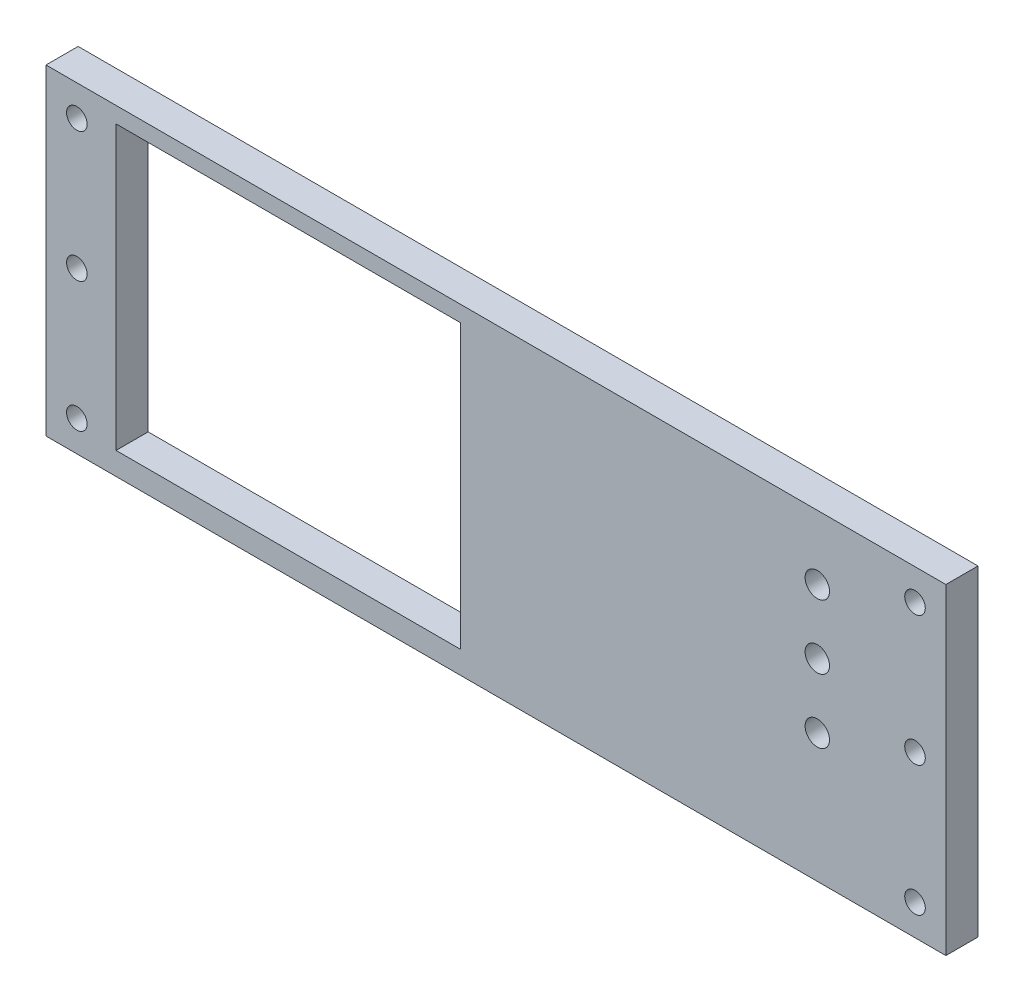
SolidWorks part; units mm, degrees
ref_plane "Front Plane" through (0, 0, 0) normal (0, 0, 1) x (1, 0, 0)
ref_plane "Top Plane" through (0, 0, 0) normal (0, 1, 0) x (1, 0, 0)
ref_plane "Right Plane" through (0, 0, 0) normal (1, 0, 0) x (0, 0, -1)
sketch "Sketch1" plane through (0, 0, 0) normal (0, 0, 1) x (1, 0, 0)
  line L0 (0, 0) -> (0, 6.176)
  line L1 (-88.9, -31.75) -> (88.9, -31.75)
  line L2 (-88.9, -31.75) -> (-88.9, 31.75)
  line L3 (-88.9, 31.75) -> (88.9, 31.75)
  line L4 (88.9, -31.75) -> (88.9, 31.75)
  line L5 (-88.9, -31.75) -> (88.9, 31.75) construction
  line L6 (-88.9, 31.75) -> (88.9, -31.75) construction
  circle A0 centre (-82.804, 25.654) radius 2.032
  circle A1 centre (-82.804, 0) radius 2.032
  circle A2 centre (-82.804, -25.654) radius 2.032
  circle A3 centre (82.804, -25.654) radius 2.032
  circle A4 centre (82.804, 0) radius 2.032
  circle A5 centre (82.804, 25.654) radius 2.032
  point P0 (0, 0)
  dimension "D3" = 4.064
  dimension "D1" = 177.8
  dimension "D2" = 63.5
  dimension "D4" = 6.096
  dimension "D5" = 6.096
  dimension "D6" = 3
extrude "Boss-Extrude1" add sketch "Sketch1" along normal blind 6.35
sketch "Sketch2" plane through (0, 0, 6.35) normal (0, 0, 1) x (1, 0, 0)
  line L0 (-88.9, -31.75) -> (88.9, -31.75) construction
  line L1 (-75.0632, -27.2905) -> (-7.0319, -27.2905)
  line L2 (-75.0632, -27.2905) -> (-75.0632, 28.5895)
  line L3 (-75.0632, 28.5895) -> (-7.0319, 28.5895)
  line L4 (-7.0319, -27.2905) -> (-7.0319, 28.5895)
  line L5 (-75.0632, -27.2905) -> (-7.0319, 28.5895) construction
  line L6 (-75.0632, 28.5895) -> (-7.0319, -27.2905) construction
  line L7 (-50.9444, 0.6495) -> (-51.3191, -30.4487)
  line L8 (-50.9444, 0.6495) -> (-50.9444, 31.75)
  line L9 (-88.9, 31.75) -> (88.9, 31.75) construction
  point P0 (-41.0476, 0.6495)
  dimension "D1" = 55.88
  dimension "D2" = 32.3995
extrude "Cut-Extrude1" cut sketch "Sketch2" against normal blind 6.35 contours L7 L8 L3 L2 L1 | L8 L7 L1 L4 L3
sketch "Sketch3" plane through (0, 0, 6.35) normal (0, 0, 1) x (1, 0, 0)
  line L0 (88.9, -31.75) -> (88.9, 31.75) construction
  line L1 (-88.9, 31.75) -> (88.9, 31.75) construction
  circle A0 centre (63.5, 19.05) radius 2.413
  dimension "D1" = 4.826
  dimension "D2" = 25.4
  dimension "D3" = 12.7
extrude "Cut-Extrude2" cut sketch "Sketch3" against normal blind 6.35
pattern_linear "LPattern1" count 3 spacing 12.7 along (0, -1, 0) of "Cut-Extrude2"
